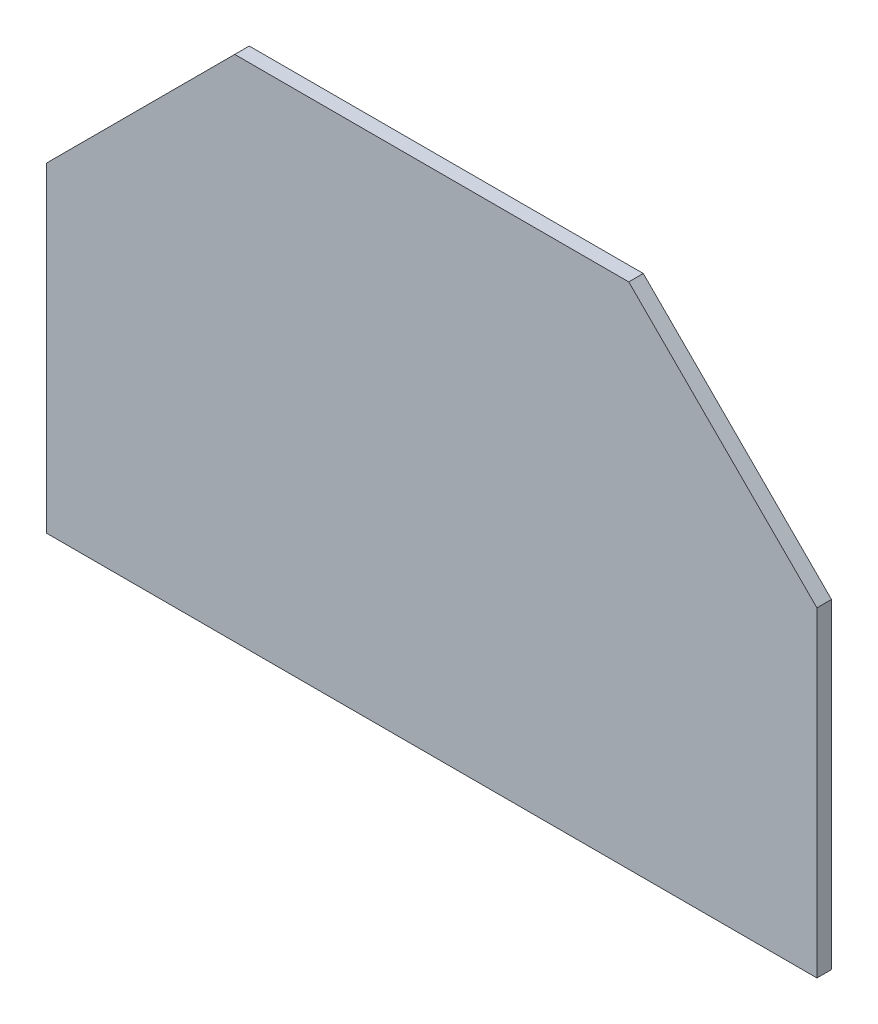
SolidWorks part; units mm, degrees
ref_plane "Front Plane" through (0, 0, 0) normal (0, 0, 1) x (1, 0, 0)
ref_plane "Top Plane" through (0, 0, 0) normal (0, 1, 0) x (1, 0, 0)
ref_plane "Right Plane" through (0, 0, 0) normal (1, 0, 0) x (0, 0, -1)
sketch "Sketch1" plane through (0, 0, 0) normal (0, 0, 1) x (1, 0, 0)
  line L0 (134.62, 23.1336) -> (68.8536, 88.9)
  line L1 (-134.62, -88.9) -> (134.62, -88.9)
  line L2 (-134.62, -88.9) -> (-134.62, 88.9) construction
  line L3 (-134.62, 88.9) -> (134.62, 88.9) construction
  line L4 (134.62, -88.9) -> (134.62, 88.9) construction
  line L5 (-134.62, -88.9) -> (134.62, 88.9) construction
  line L6 (-134.62, 88.9) -> (134.62, -88.9) construction
  line L7 (-68.8536, 88.9) -> (-134.62, 23.1336)
  line L8 (68.8536, 88.9) -> (-68.8536, 88.9)
  line L9 (134.62, 23.1336) -> (134.62, -88.9)
  line L10 (-134.62, 23.1336) -> (-134.62, -88.9)
  point P0 (0, 0)
  dimension "D1" = 269.24
  dimension "D2" = 177.8
  dimension "D3" = 135
  dimension "D4" = 135
extrude "Boss-Extrude1" add sketch "Sketch1" along normal blind 5.08
